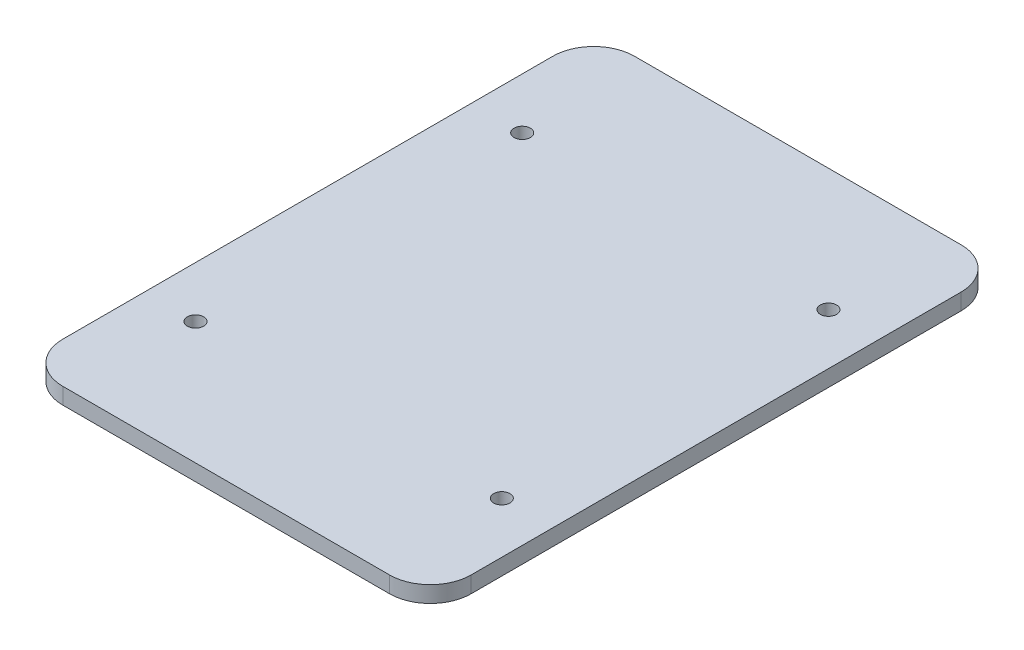
SolidWorks part; units mm, degrees
ref_plane "前视基准面" through (0, 0, 0) normal (0, 0, 1) x (1, 0, 0)
ref_plane "上视基准面" through (0, 0, 0) normal (0, 1, 0) x (1, 0, 0)
ref_plane "右视基准面" through (0, 0, 0) normal (1, 0, 0) x (0, 0, -1)
other "Configuration Table"
sketch "草图1" plane through (0, 0, 0) normal (0, 1, 0) x (1, 0, 0)
  line L0 (37.5, -40) -> (-37.5, -40) construction
  line L1 (-50, -70) -> (50, -70)
  line L2 (-50, -70) -> (-50, 70)
  line L3 (-50, 70) -> (50, 70)
  line L4 (50, -70) -> (50, 70)
  line L5 (-50, -70) -> (50, 70) construction
  line L6 (-50, 70) -> (50, -70) construction
  line L7 (37.5, -40) -> (37.5, 40) construction
  line L8 (37.5, 40) -> (-37.5, 40) construction
  line L9 (-37.5, -40) -> (-37.5, 40) construction
  line L10 (37.5, -40) -> (-37.5, 40) construction
  line L11 (37.5, 40) -> (-37.5, -40) construction
  circle A0 centre (-37.5, 40) radius 2
  circle A1 centre (37.5, 40) radius 2
  circle A2 centre (37.5, -40) radius 2
  circle A3 centre (-37.5, -40) radius 2
  point P0 (0, 0)
  point P6 (0, 0)
  dimension "D3" = 4
  dimension "D1" = 75
  dimension "D2" = 80
  dimension "D4" = 100
  dimension "D5" = 140
extrude "凸台-拉伸1" add sketch "草图1" along normal blind 4
fillet "圆角1" radius 10 4 edges at (-50, 2, -70) (50, 2, -70) (-50, 2, 70) (50, 2, 70)
